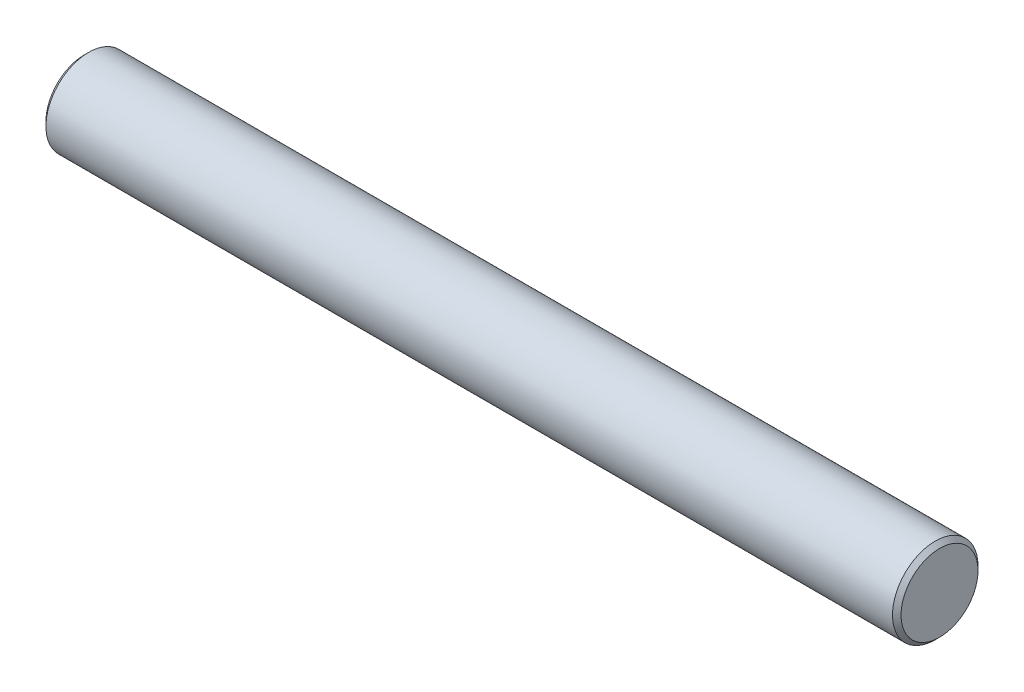
SolidWorks part; units mm, degrees
ref_plane "Front" through (0, 0, 0) normal (0, 0, 1) x (1, 0, 0)
ref_plane "Top" through (0, 0, 0) normal (0, 1, 0) x (1, 0, 0)
ref_plane "Right" through (0, 0, 0) normal (1, 0, 0) x (0, 0, -1)
sketch "Sketch1" plane through (0, 0, 0) normal (-1, 0, 0) x (0, -1, 0)
  circle A0 centre (0, 0) radius 2.5
  dimension "D1" = 5
extrude "Boss-Extrude1" add sketch "Sketch1" against normal blind 50
chamfer "Chamfer1" distance 0.25 angle 45 2 edges at (0, 0, -2.5) (50, 0, -2.5)
